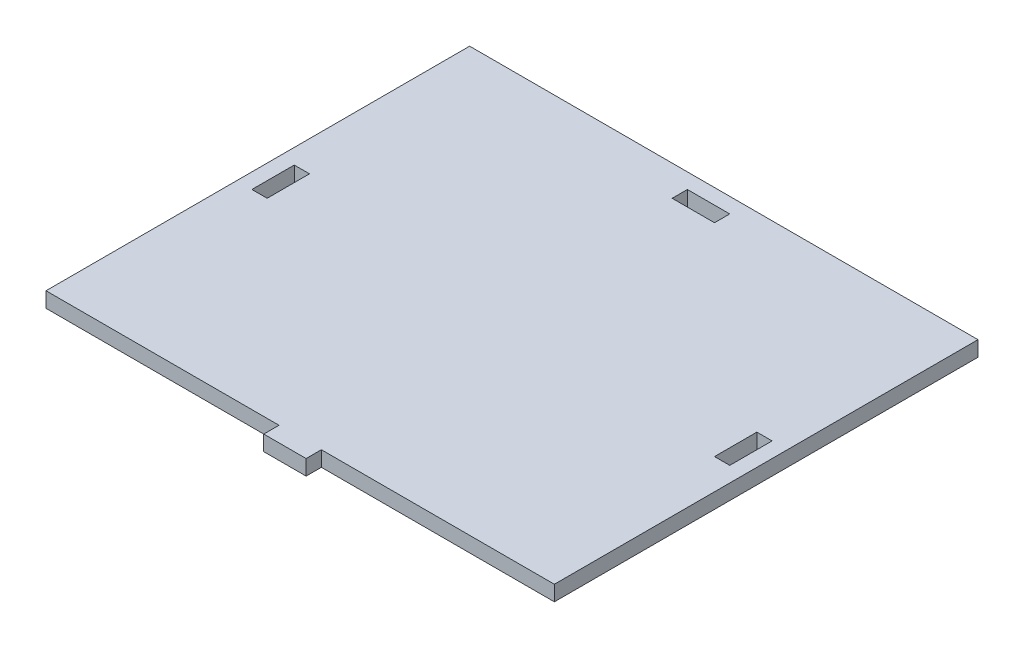
SolidWorks part; units mm, degrees
ref_plane "Front Plane" through (0, 0, 0) normal (0, 0, 1) x (1, 0, 0)
ref_plane "Top Plane" through (0, 0, 0) normal (0, 1, 0) x (1, 0, 0)
ref_plane "Right Plane" through (0, 0, 0) normal (1, 0, 0) x (0, 0, -1)
sketch "Sketch1" plane through (0, 0, 0) normal (0, 1, 0) x (1, 0, 0)
  line L0 (0, 250) -> (0, 0) construction
  line L1 (-300, 250) -> (300, 250)
  line L2 (-300, 250) -> (-300, -250)
  line L3 (-300, -250) -> (-25, -250)
  line L4 (300, 250) -> (300, -250)
  line L5 (-300, 250) -> (300, -250) construction
  line L6 (-300, -250) -> (300, 250) construction
  line L7 (300, 0) -> (-300, 0) construction
  line L8 (-264, -25) -> (-282, -25)
  line L9 (-25, 232) -> (25, 232)
  line L10 (-25, 232) -> (-25, 214)
  line L11 (-25, 214) -> (25, 214)
  line L12 (25, 232) -> (25, 214)
  line L13 (-25, 232) -> (25, 214) construction
  line L14 (-25, 214) -> (25, 232) construction
  line L15 (264, 25) -> (282, 25)
  line L16 (264, 25) -> (264, -25)
  line L17 (264, -25) -> (282, -25)
  line L18 (282, 25) -> (282, -25)
  line L19 (264, 25) -> (282, -25) construction
  line L20 (264, -25) -> (282, 25) construction
  line L21 (-282, 25) -> (-282, -25)
  line L22 (-264, 25) -> (-282, 25)
  line L23 (-264, 25) -> (-264, -25)
  line L26 (-25, -250) -> (-25, -268)
  line L27 (-25, -268) -> (25, -268)
  line L28 (25, -250) -> (25, -268)
  line L31 (25, -250) -> (300, -250)
  point P0 (0, 0)
  point P10 (0, 223)
  point P15 (273, 0)
  dimension "D1" = 600
  dimension "D2" = 500
  dimension "D3" = 18
  dimension "D4" = 50
  dimension "D5" = 18
  dimension "D6" = 18
  dimension "D7" = 18
  dimension "D8" = 50
  dimension "D9" = 50
extrude "Boss-Extrude1" add sketch "Sketch1" along normal blind 18
